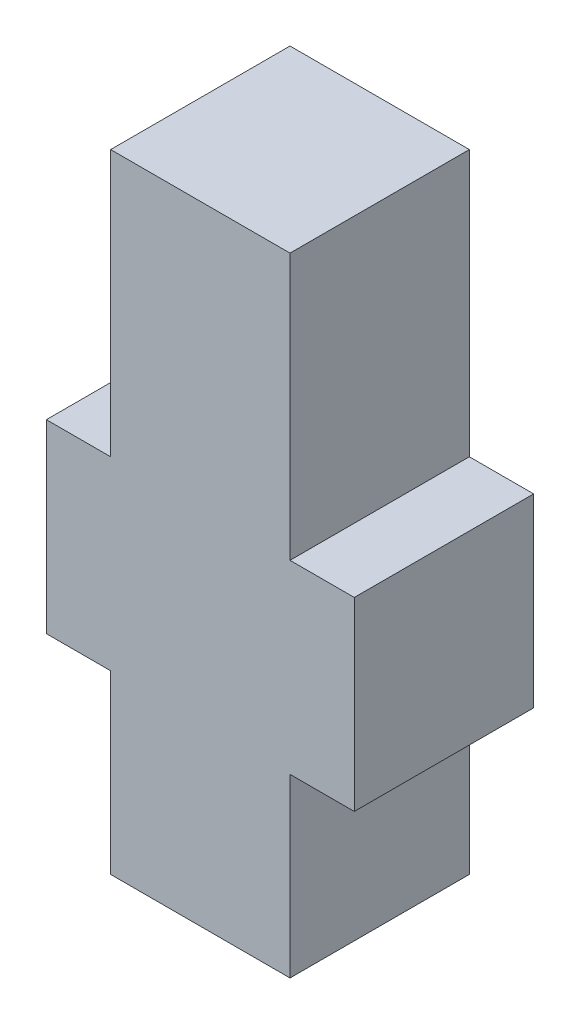
SolidWorks part; units mm, degrees
ref_plane "Спереди" through (0, 0, 0) normal (0, 0, 1) x (1, 0, 0)
ref_plane "Сверху" through (0, 0, 0) normal (0, 1, 0) x (1, 0, 0)
ref_plane "Справа" through (0, 0, 0) normal (1, 0, 0) x (0, 0, -1)
other "Configuration Table"
sketch "Канал_6" plane through (0, 0, 0) normal (0, 0, 1) x (1, 0, 0)
  line L0 (-3, -21) -> (3, -21)
  line L1 (3, -21) -> (3, 0)
  line L2 (3, 0) -> (-3, 0)
  line L3 (-3, 0) -> (-3, -21)
  line L4 (-3, -21) -> (3, 0) construction
  point P4 (0, -10.5)
  dimension "Ширина" = 6
  dimension "Глубина" = 21
  dimension "Положение_ОтКромки" = 10.5
extrude "Канал_сквозной" add sketch "Канал_6" along normal blind 6
sketch "Карман_гайки" plane through (0, 0, 0) normal (0, 0, 1) x (1, 0, 0)
  line L0 (-5.15, -15.1) -> (5.15, -15.1)
  line L1 (5.15, -15.1) -> (5.15, -8.9)
  line L2 (5.15, -8.9) -> (-5.15, -8.9)
  line L3 (-5.15, -8.9) -> (-5.15, -15.1)
  line L4 (-5.15, -15.1) -> (5.15, -8.9) construction
  point P4 (0, -12)
  dimension "Ширина" = 10.3
  dimension "Глубина" = 6.2
  dimension "Положение_ОтКромки" = 12
extrude "Гайка_10_3х6_2" add sketch "Карман_гайки" along normal blind 6
equation "\"D1@Гайка_10_3х6_2\"  = \"Толщина вертикальных стенок\""
equation "\"D1@Канал_сквозной\"  = \"Толщина вертикальных стенок\""
equation "\"Фанера\"=6"
equation "\"Ширина шипа\"=16"
equation "\"Межосевое шипов\"=40"
equation "\"Посадочный зазор\"=0.15"
equation "\"Основная фреза\"=6"
equation "\"Мелкая фреза\"=6"
equation "\"Запас разгрузки\"=0.05"
equation "\"Ширина образца\"=84"
equation "\"Высота образца\"=50"
equation "\"Канал М6\"=6"
equation "\"Гайка под ключ\"=10.3"
equation "\"Длина кармана гайки\"=6.2"
equation "\"Отступ гайки\"=12"
equation "\"Ширина@Канал_6\" = \"Канал М6\""
equation "\"Глубина@Канал_6\" = 21"
equation "\"Положение_ОтКромки@Канал_6\" =  -  (  - 10.5 ) "
equation "\"Ширина@Карман_гайки\" = \"Гайка под ключ\""
equation "\"Глубина@Карман_гайки\" = \"Длина кармана гайки\""
equation "\"Положение_ОтКромки@Карман_гайки\" =  -  (  - \"Отступ гайки\" ) "
equation "\"Ширина груза\"= 160"
equation "\"Глубина груза\"= 240"
equation "\"Высота груза\"= 160"
equation "\"Ширина ячейки\"= \"Ширина груза\" + 10"
equation "\"Глубина ячейки\"= \"Глубина груза\" + 10"
equation "\"Высота ячейки\"= \"Высота груза\" + 10 + 13"
equation "\"Колво ячеек ширина\"= 2"
equation "\"Колво ячеек высота\"= 2"
equation "\"Толщина стенки\"= \"Толщина тонких панелей\""
equation "\"Крепление дверцы\"= 5 "
equation "\"Ширина рейки\"= \"Толщина шестерни\""
equation "\"Высота рейки\"= 20"
equation "\"Высота пола\"= 2*\"Толщина тонких панелей\""
equation "\"Колво полозьев\"= 5"
equation "\"Отступ рейки\"= 20"
equation "\"Глубина каретки\"= \"Глубина ячейки\" + 30 + \"Мотор Y высота корпуса\" + 20"
equation "\"Длинна рейки\"= (\"Ширина ячейки\"+\"Толщина вертикальных стенок\"+\"Крепление дверцы\")*\"Колво ячеек ширина\"+\"Ширина ячейки выгрузки\"*\"Колво выгрузки\"+\"Толщина вертикальных стенок\"+2*\"Отступ крепления мотора фиксации\"-\"Крепление дверцы\"*\"Колво ячеек ширина\""
equation "\"Отступ шпильки\"= 26"
equation "\"Диаметр шпильки\"= 5"
equation "\"Длинна шпильки\"= (\"Высота ячейки\"+\"Толщина горизонтальных плит\"+\"Высота пола\")*\"Колво ячеек высота\"+2*(\"Толщина горизонтальных плит\"+\"Отступ рейки\")"
equation "\"Ширина пластины\"= 50  "
equation "\"Высота зона выгрузки\"= \"Высота ячейки\" * 2 + \"Толщина стенки\" * 2"
equation "\"Колво выгрузки\"= 1"
equation "\"Ширина ячейки выгрузки\"= \"Ширина ячейки\"+\"Толщина вертикальных стенок\"+2*\"Отступ крепления мотора фиксации\""
equation "\"Отступ крепления мотора фиксации\"= (\"Ширина пластины\"+20-\"Толщина вертикальных стенок\")/2"
equation "\"Мотор X ширина корпуса\"= 42.3"
equation "\"Мотор X высота корпуса\"= 42.3"
equation "\"Мотор X длина корпуса\"= 40"
equation "\"Мотор X вылет вала\"= 19.8"
equation "\"Мотор Y ширина корпуса\"= 42.3"
equation "\"Мотор Y высота корпуса\"= 42.3"
equation "\"Мотор Y длина корпуса\"= 48"
equation "\"Мотор Y вылет вала\"= 30"
equation "\"Мотор Z ширина корпуса\"= 42"
equation "\"Мотор Z высота корпуса\"= 42"
equation "\"Мотор Z длина корпуса\"= 40"
equation "\"Мотор Z вылет вала\"= 23"
equation "\"Мотор диаметр вала ПРЕДВ\"= 5"
equation "\"Мотор шаг крепления ПРЕДВ\"= 31"
equation "\"Мотор диаметр отверстий ПРЕДВ\"= 3"
equation "\"Мотор глубина отверстий ПРЕДВ\"= 4.5"
equation "\"Мотор диаметр буртика ПРЕДВ\"= 22"
equation "\"Мотор высота буртика ПРЕДВ\"= 2"
equation "\"Мотор диаметр шкива ПРЕДВ\"= 16"
equation "\"Мотор длина шкива ПРЕДВ\"= 12"
equation "\"Мотор отступ шкива ПРЕДВ\"= 5"
equation "\"Мотор X шаг градусов\"= 1.8"
equation "\"Мотор Y шаг градусов\"= 1.8"
equation "\"Мотор Z шаг градусов\"= 1.8"
equation "\"Мотор Y диаметр ротора\"= 25.78"
equation "\"Толщина шестерни\"= 10"
equation "\"Толщина тонких панелей\"= 6"
equation "\"Толщина вертикальных стенок\"= 6"
equation "\"Толщина горизонтальных плит\"= 6"
equation "\"Базовая высота корпуса\"= (\"Высота ячейки\"+\"Толщина тонких панелей\"+\"Высота пола\")*\"Колво ячеек высота\"+6*\"Толщина тонких панелей\"+\"Мотор X ширина корпуса\"+\"Мотор Y ширина корпуса\"+75"
equation "\"Высота корпуса\"= (\"Высота ячейки\"+\"Толщина горизонтальных плит\"+\"Высота пола\")*\"Колво ячеек высота\"+2*\"Толщина горизонтальных плит\"+4*\"Толщина тонких панелей\"+\"Мотор X ширина корпуса\"+\"Мотор Y ширина корпуса\"+75"
equation "\"Смещение центра корпуса\"= (\"Высота корпуса\"-\"Базовая высота корпуса\")/2-(\"Толщина горизонтальных плит\"-\"Толщина тонких панелей\")"
equation "\"Отметка пола\"= -\"Базовая высота корпуса\"/2+\"Толщина тонких панелей\""
equation "\"Отметка потолка\"= \"Отметка пола\"+\"Высота корпуса\"-2*\"Толщина горизонтальных плит\""
equation "\"Отметка верхней полки\"= \"Отметка потолка\"-(28+\"Толщина тонких панелей\")-\"Высота ячейки\"-\"Высота пола\""
equation "\"Отметка нижней полки\"= \"Отметка верхней полки\"-\"Высота ячейки\"-\"Высота пола\"-\"Толщина горизонтальных плит\""
